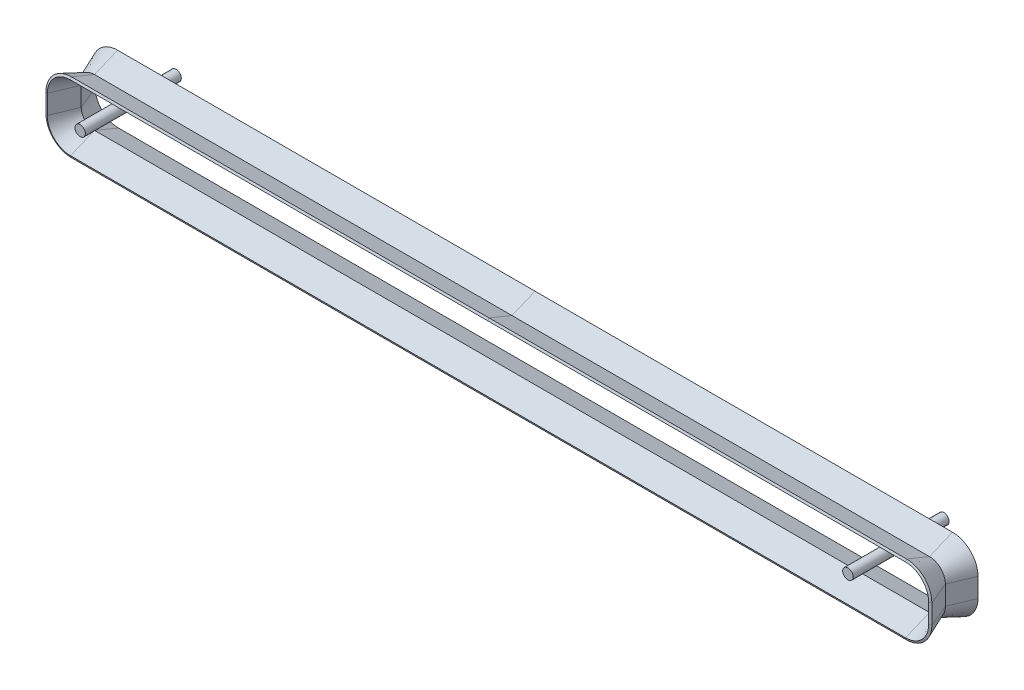
SolidWorks part; units mm, degrees
ref_plane "Alzado" through (0, 0, 0) normal (0, 0, 1) x (1, 0, 0)
ref_plane "Planta" through (0, 0, 0) normal (0, 1, 0) x (1, 0, 0)
ref_plane "Vista lateral" through (0, 0, 0) normal (1, 0, 0) x (0, 0, -1)
sketch "Croquis58" plane through (0, 0, 0) normal (1, 0, 0) x (0, 0, -1)
  line L0 (0, 0) -> (-50, 20.7107)
  line L1 (0, 0) -> (0, 38.1737) construction
  line L2 (0, 0) -> (50, 20.7107)
  line L3 (0, 5.412) -> (48.0866, 25.3301)
  line L4 (0, 5.412) -> (-48.0866, 25.3301)
  line L5 (-48.0866, 25.3301) -> (-50, 20.7107)
  line L6 (48.0866, 25.3301) -> (50, 20.7107)
  dimension "D1" = 100
  dimension "D2" = 135
  dimension "D3" = 5
sketch "Croquis59" plane through (0, 0, 0) normal (0, 0, 1) x (1, 0, 0)
  line L0 (-870, 2.2928) -> (870, 2.2928)
  line L1 (0, 0) -> (0, 20.7107) construction
  line L2 (900, -27.7072) -> (900, -67.7072)
  line L3 (870, -97.7072) -> (-870, -97.7072)
  line L4 (0, 2.2928) -> (0, -97.7072) construction
  line L5 (-900, -27.7072) -> (-900, -67.7072)
  arc A0 (900, -27.7072) -> (870, 2.2928) centre (870, -27.7072) ccw
  arc A1 (870, -97.7072) -> (900, -67.7072) centre (870, -67.7072) ccw
  arc A2 (-870, -97.7072) -> (-900, -67.7072) centre (-870, -67.7072) cw
  arc A3 (-900, -27.7072) -> (-870, 2.2928) centre (-870, -27.7072) cw
  point P8 (900, 2.2928)
  point P11 (900, -97.7072)
  point P18 (-900, -97.7072)
  point P19 (-900, 2.2928)
  dimension "D4" = 30
  dimension "D5" = 30
  dimension "D1" = 900
  dimension "D2" = 100
sweep "Barrer8" add profiles "Croquis58" path "Croquis59"
sketch "Croquis61" plane through (0, 0, 0) normal (0, 0, 1) x (1, 0, 0)
  line L0 (0, 0) -> (0, -98.0371) construction
  circle A0 centre (-800, -10.861) radius 10.861
  circle A1 centre (800, -10.861) radius 10.861
  dimension "D1" = 800
ref_plane "Plano2" through (0, 0, 50) normal (0, 0, 1) x (1, 0, 0)
extrude "Saliente-Extruir2" add sketch "Croquis61" along normal mid plane 200 separate body
